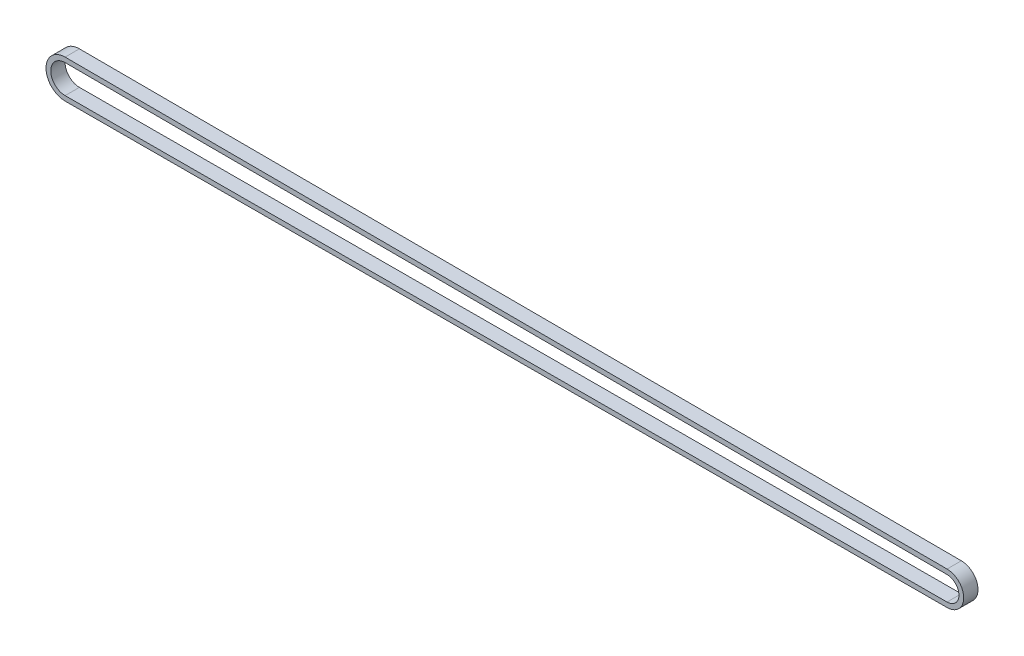
SolidWorks part; units mm, degrees
ref_plane "Plano frontal" through (0, 0, 0) normal (0, 0, 1) x (1, 0, 0)
ref_plane "Plano superior" through (0, 0, 0) normal (0, 1, 0) x (1, 0, 0)
ref_plane "Plano direito" through (0, 0, 0) normal (1, 0, 0) x (0, 0, -1)
sketch "Esboço1" plane through (0, 0, 0) normal (0, 0, 1) x (1, 0, 0)
  line L0 (0, 0) -> (-370, 0) construction
  line L1 (-369.9838, 6) -> (0.0135, 5)
  line L2 (-369.9838, -6) -> (0.0135, -5)
  line L3 (-369.9784, 8) -> (0.0189, 7)
  line L4 (-369.9784, -8) -> (0.0189, -7)
  arc A0 (0.0135, 5) -> (0.0135, -5) centre (0, 0) cw
  arc A1 (-369.9838, 6) -> (-369.9838, -6) centre (-370, 0) ccw
  arc A2 (0.0189, 7) -> (0.0189, -7) centre (0, 0) cw
  arc A3 (-369.9784, 8) -> (-369.9784, -8) centre (-370, 0) ccw
  dimension "D1" = 6
  dimension "D2" = 5
  dimension "D3" = 370
  dimension "D4" = 2
extrude "Ressalto-extrusão1" add sketch "Esboço1" along normal blind 6
